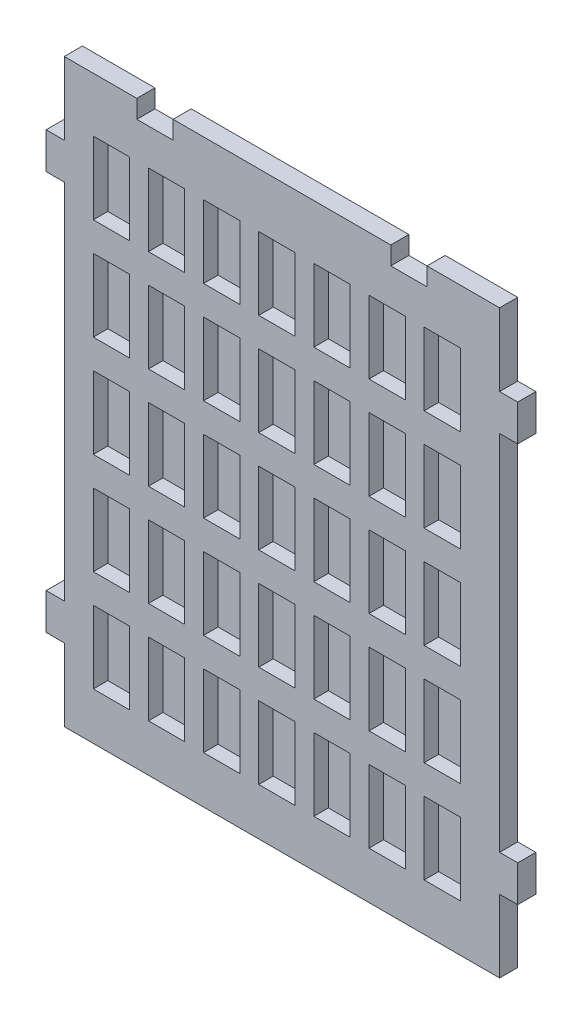
SolidWorks part; units mm, degrees
ref_plane "Front Plane" through (0, 0, 0) normal (0, 0, 1) x (1, 0, 0)
ref_plane "Top Plane" through (0, 0, 0) normal (0, 1, 0) x (1, 0, 0)
ref_plane "Right Plane" through (0, 0, 0) normal (1, 0, 0) x (0, 0, -1)
sketch "Sketch1" plane through (0, 0, 0) normal (0, 0, 1) x (1, 0, 0)
  line L0 (19.05, 0) -> (57.15, 0)
  line L1 (0, 0) -> (12.7, 0)
  line L2 (0, 0) -> (0, -12.7)
  line L3 (0, -101.6) -> (12.7, -101.6)
  line L4 (76.2, -19.05) -> (76.2, -82.55)
  line L5 (63.5, 0) -> (76.2, 0)
  line L6 (12.7, 0) -> (12.7, -3.175)
  line L7 (12.7, -3.175) -> (19.05, -3.175)
  line L8 (19.05, 0) -> (19.05, -3.175)
  line L9 (0, -19.05) -> (0, -82.55)
  line L10 (57.15, 0) -> (57.15, -3.175)
  line L11 (57.15, -3.175) -> (63.5, -3.175)
  line L12 (63.5, 0) -> (63.5, -3.175)
  line L13 (76.2, -12.7) -> (79.375, -12.7)
  line L14 (76.2, -88.9) -> (76.2, -101.6)
  line L15 (76.2, -19.05) -> (79.375, -19.05)
  line L16 (79.375, -12.7) -> (79.375, -19.05)
  line L17 (76.2, -82.55) -> (79.375, -82.55)
  line L18 (63.5, -101.6) -> (76.2, -101.6)
  line L19 (76.2, -88.9) -> (79.375, -88.9)
  line L20 (79.375, -82.55) -> (79.375, -88.9)
  line L21 (12.7, -101.6) -> (63.5, -101.6)
  line L25 (0, -88.9) -> (0, -101.6)
  line L29 (0, -88.9) -> (-3.175, -88.9)
  line L31 (0, -82.55) -> (-3.175, -82.55)
  line L32 (-3.175, -88.9) -> (-3.175, -82.55)
  line L33 (0, -19.05) -> (-3.175, -19.05)
  line L34 (76.2, 0) -> (76.2, -12.7)
  line L35 (0, -12.7) -> (-3.175, -12.7)
  line L36 (-3.175, -19.05) -> (-3.175, -12.7)
  dimension "D3" = 12.7
  dimension "D4" = 6.35
  dimension "D5" = 3.175
  dimension "D6" = 6.35
  dimension "D7" = 3.175
  dimension "D8" = 12.7
  dimension "D9" = 101.6
  dimension "D10" = 6.35
  dimension "D11" = 3.175
  dimension "D12" = 3.175
  dimension "D13" = 6.35
  dimension "D14" = 12.7
  dimension "D15" = 76.2
  dimension "D21" = 3.175
  dimension "D22" = 6.35
  dimension "D23" = 12.7
  dimension "D24" = 12.7
  dimension "D25" = 6.35
  dimension "D26" = 3.175
  dimension "D27" = 3.175
  dimension "D29" = 3.175
  dimension "D30" = 12.7
extrude "Boss-Extrude1" add sketch "Sketch1" along normal blind 3.175
sketch "Sketch2" plane through (0, 0, 3.175) normal (0, 0, 1) x (1, 0, 0)
  line L0 (12.7, -3.175) -> (19.05, -3.175) construction
  line L1 (5.08, -9.525) -> (11.43, -9.525)
  line L2 (5.08, -9.525) -> (5.08, -22.225)
  line L3 (5.08, -22.225) -> (11.43, -22.225)
  line L4 (11.43, -9.525) -> (11.43, -22.225)
  line L5 (5.08, -9.525) -> (11.43, -22.225) construction
  line L6 (5.08, -22.225) -> (11.43, -9.525) construction
  line L7 (0, -19.05) -> (0, -82.55) construction
  point P0 (8.255, -15.875)
  dimension "D1" = 6.35
  dimension "D2" = 6.35
  dimension "D3" = 12.7
  dimension "D4" = 5.08
extrude "Cut-Extrude1" cut sketch "Sketch2" against normal blind 2.54
pattern_linear "LPattern1" count 7 spacing 9.652 along (1, 0, 0) count 5 spacing 17.78 along (0, -1, 0) of "Cut-Extrude1"
